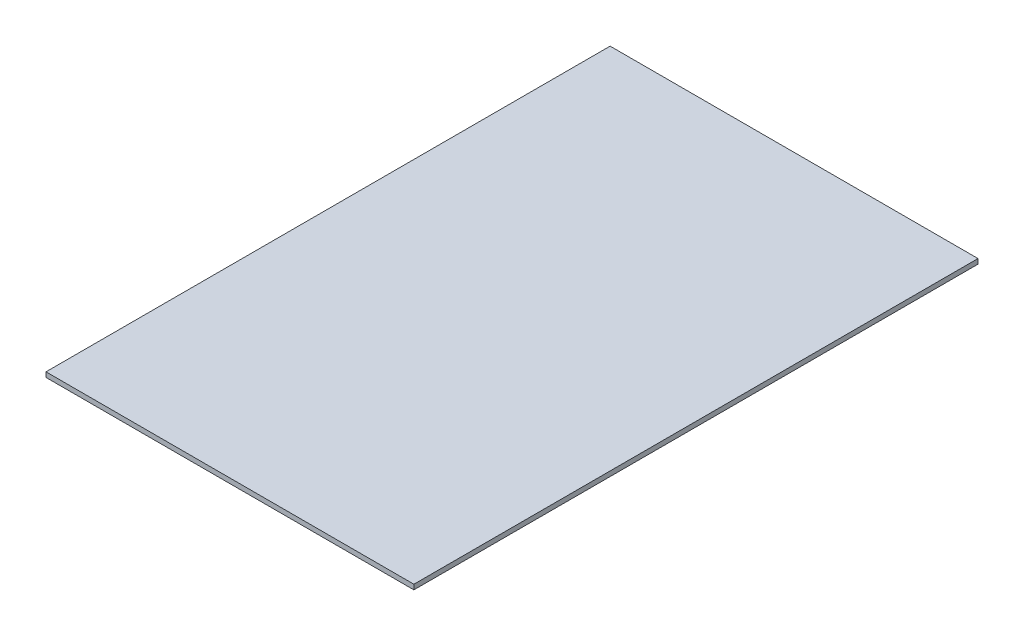
SolidWorks part; units mm, degrees
ref_plane "Front Plane" through (0, 0, 0) normal (0, 0, 1) x (1, 0, 0)
ref_plane "Top Plane" through (0, 0, 0) normal (0, 1, 0) x (1, 0, 0)
ref_plane "Right Plane" through (0, 0, 0) normal (1, 0, 0) x (0, 0, -1)
sketch "Sketch2" plane through (0, 0, 0) normal (0, 1, 0) x (1, 0, 0)
  line L11 (374.6787, -144.9804) -> (374.6787, 430.0196)
  line L12 (-0.3213, -144.9804) -> (374.6787, -144.9804)
  line L13 (-0.3213, 430.0196) -> (-0.3213, -144.9804)
  line L14 (374.6787, 430.0196) -> (-0.3213, 430.0196)
  line L15 (374.6787, -144.9804) -> (374.6787, 430.0196)
  line L16 (-0.3213, -144.9804) -> (374.6787, -144.9804)
  line L17 (-0.3213, 430.0196) -> (-0.3213, -144.9804)
  line L18 (374.6787, 430.0196) -> (-0.3213, 430.0196)
  dimension "D1" = 2.5
extrude "Boss-Extrude2" add sketch "Sketch2" against normal blind 5 from surface
